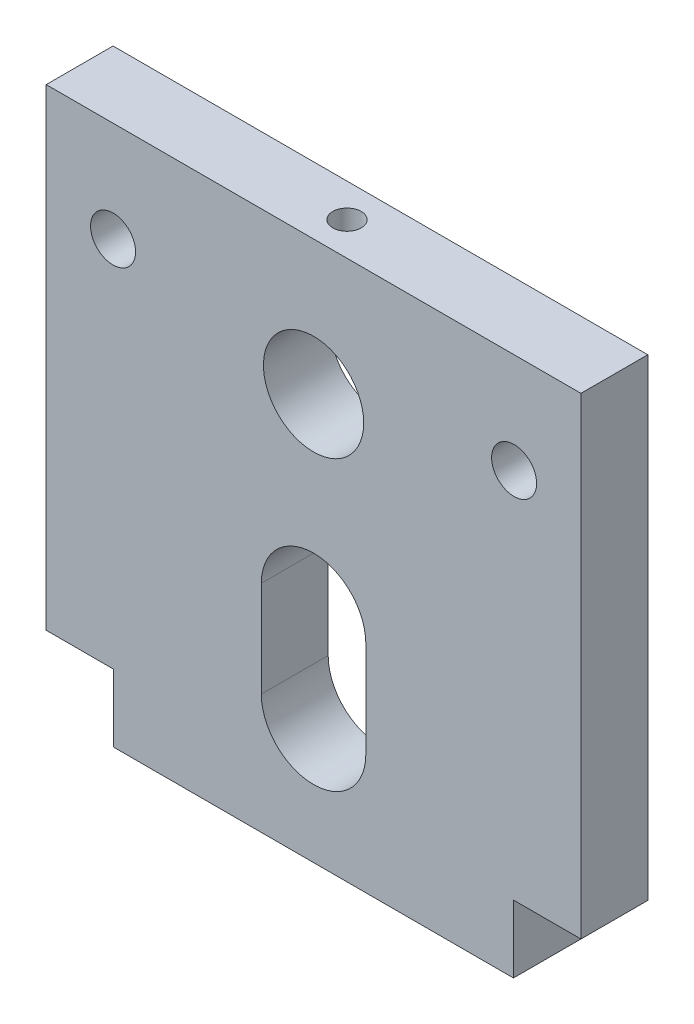
SolidWorks part; units mm, degrees
ref_plane "Front Plane" through (0, 0, 0) normal (0, 0, 1) x (1, 0, 0)
ref_plane "Top Plane" through (0, 0, 0) normal (0, 1, 0) x (1, 0, 0)
ref_plane "Right Plane" through (0, 0, 0) normal (1, 0, 0) x (0, 0, -1)
sketch "Sketch1" plane through (0, 0, 0) normal (0, 0, 1) x (1, 0, 0)
  line L0 (-25.6833, 38.8666) -> (25.1167, 38.8666)
  line L1 (25.1167, 38.8666) -> (25.1167, -6.0279)
  line L2 (25.1167, -6.0279) -> (18.7032, -6.0279)
  line L3 (18.7032, -6.0279) -> (18.7032, -12.4414)
  line L4 (18.7032, -12.4414) -> (-19.2698, -12.4414)
  line L5 (-19.2698, -12.4414) -> (-19.2698, -6.0279)
  line L6 (-19.2698, -6.0279) -> (-25.6833, -6.0279)
  line L7 (-25.6833, -6.0279) -> (-25.6833, 38.8666)
  dimension "D1" = 50.8
  dimension "D2" = 44.8945
  dimension "D3" = 6.4135
  dimension "D4" = 6.4135
  dimension "D5" = 6.4135
  dimension "D6" = 6.4135
extrude "Boss-Extrude1" add sketch "Sketch1" along normal blind 6.35 contours L1 L2 L3 L4 L5 L6 L7 L0
sketch "Sketch2" plane through (0, 0, 6.35) normal (0, 0, 1) x (1, 0, 0)
  line L0 (-0.2833, -12.4414) -> (-0.2833, 38.8666) construction
  line L1 (18.7032, -12.4414) -> (-19.2698, -12.4414) construction
  line L2 (-25.6833, 38.8666) -> (25.1167, 38.8666) construction
  line L3 (-25.6833, 21.1882) -> (25.1167, 21.1882) construction
  line L4 (-25.6833, -6.0279) -> (-25.6833, 38.8666) construction
  line L5 (25.1167, 38.8666) -> (25.1167, -6.0279) construction
  line L6 (-25.6833, 31.1831) -> (25.1167, 31.1831) construction
  circle A0 centre (-0.2833, 26.1031) radius 4.7625
  point P14 (0, 0)
  point P17 (-25.6833, 26.1031)
  dimension "D3" = 9.525
  dimension "D1" = 17.6784
  dimension "D2" = 7.6835
extrude "Cut-Extrude1" cut sketch "Sketch2" against normal blind 6.35
sketch "Sketch3" plane through (0, 0, 6.35) normal (0, 0, 1) x (1, 0, 0)
  line L0 (-19.3333, 38.8666) -> (-19.3333, -6.0279) construction
  line L1 (-25.6833, 38.8666) -> (25.1167, 38.8666) construction
  line L2 (-19.2698, -6.0279) -> (-25.6833, -6.0279) construction
  line L3 (-25.6833, -6.0279) -> (-25.6833, 38.8666) construction
  line L4 (-25.6833, 29.3416) -> (25.1167, 29.3416) construction
  line L5 (25.1167, 38.8666) -> (25.1167, -6.0279) construction
  line L6 (18.7667, 38.8666) -> (18.7667, -6.0279) construction
  line L7 (25.1167, -6.0279) -> (18.7032, -6.0279) construction
  circle A0 centre (-19.3333, 29.3416) radius 2.14
  circle A1 centre (18.7667, 29.3416) radius 2.14
  point P16 (-19.3333, 29.3416)
  point P17 (18.7667, 29.3416)
  dimension "D4" = 4.2799
  dimension "D5" = 4.2799
  dimension "D1" = 6.35
  dimension "D2" = 9.525
  dimension "D3" = 44.45
extrude "Cut-Extrude2" cut sketch "Sketch3" against normal blind 6.35
sketch "Sketch4" plane through (0, 0, 6.35) normal (0, 0, 1) x (1, 0, 0)
  line L0 (-0.2833, 26.1031) -> (-0.2833, -13.6006) construction
  line L1 (-19.2698, -6.0279) -> (18.7032, -6.0279) construction
  line L2 (-25.6833, 13.0221) -> (25.1167, 13.0221) construction
  line L3 (-25.6833, -6.0279) -> (-25.6833, 38.8666) construction
  line L4 (25.1167, 38.8666) -> (25.1167, -6.0279) construction
  line L5 (-25.6833, 3.4971) -> (25.1167, 3.4971) construction
  line L8 (-5.2463, 13.0221) -> (4.6798, 13.0221)
  line L9 (-5.2463, 13.0221) -> (-5.2463, -6.0279)
  line L10 (-5.2463, -6.0279) -> (4.6798, -6.0279)
  line L11 (4.6798, 13.0221) -> (4.6798, -6.0279)
  line L12 (-5.2463, 13.0221) -> (4.6798, -6.0279) construction
  line L13 (-5.2463, -6.0279) -> (4.6798, 13.0221) construction
  point P17 (-0.2833, 3.4971)
  dimension "D1" = 19.05
  dimension "D2" = 9.525
  dimension "D3" = 9.9261
sketch "Sketch6" plane through (0, 0, 6.35) normal (0, 0, 1) x (1, 0, 0)
  line L0 (-0.2833, 8.0607) -> (-0.2833, -1.0583) construction
  line L1 (-0.2833, 26.1031) -> (-0.2833, -13.6006) construction
  line L2 (4.6798, 8.0607) -> (4.6798, -1.0583)
  line L3 (-5.2463, 8.0607) -> (-5.2463, -1.0583)
  line L6 (4.6798, 13.0221) -> (4.6798, -6.0279) construction
  arc A0 (4.6798, 8.0607) -> (-5.2463, 8.0607) centre (-0.2833, 8.0607) ccw
  arc A1 (-5.2463, -1.0583) -> (4.6798, -1.0583) centre (-0.2833, -1.0583) ccw
  point P4 (-0.2833, 3.5012)
  point P9 (4.6798, 6.7356)
  point P11 (-0.2833, 8.0607)
  point P12 (-0.2833, -0.9848)
  point P14 (0, 0)
  point P15 (-0.2833, -1.0466)
  point P16 (-0.2833, -1.0583)
  dimension "D1" = 9.119
extrude "Cut-Extrude4" cut sketch "Sketch6" against normal blind 6.35 contours A0 L3 A1 L2
sketch "Sketch7" plane through (0, 38.8666, 0) normal (0, 1, 0) x (1, 0, 0)
  line L0 (-0.2833, -6.35) -> (-0.2833, -3.175) construction
  line L2 (-5.2463, -6.35) -> (4.6798, -6.35) construction
  point P4 (0, 0)
  dimension "D1" = 3.175
hole_wizard "#6-32 Tapped Hole1" positions "Sketch12" profile "Sketch13" tap size "#6-32" standard "ANSI Inch"
sketch "Sketch12" plane through (0, 38.8666, 0) normal (0, 1, 0) x (1, 0, 0)
  point P0 (-0.2833, -3.175)
sketch "Sketch13" plane through (-0.2833, 38.8666, 3.175) normal (1, 0, 0) x (0, 0, 1)
  line L0 (0, 0) -> (0, 8.001)
  line L1 (0, 8.001) -> (1.3525, 8.001)
  line L2 (1.3525, 8.001) -> (1.3525, 0)
  line L5 (1.3525, 0) -> (0, 0)
  line L11 (0, -6.35) -> (0, 107.95) construction
  dimension "Thru Tap Drill Dia." = 2.7051
  dimension "Thru Tap Drill Depth" = 8.001
cosmetic thread "Hole Thread3" parameters "D2"=3.5052
